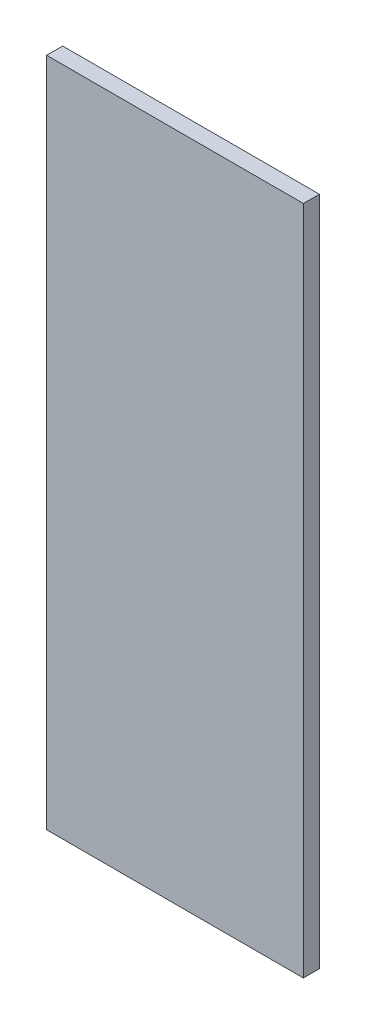
SolidWorks part; units mm, degrees
material "AISI 1020"
ref_plane "Спереди" through (0, 0, 0) normal (0, 0, 1) x (1, 0, 0)
ref_plane "Сверху" through (0, 0, 0) normal (0, 1, 0) x (1, 0, 0)
ref_plane "Справа" through (0, 0, 0) normal (1, 0, 0) x (0, 0, -1)
sketch "Эскиз1" plane through (0, 0, 0) normal (0, 0, 1) x (1, 0, 0)
  line L1 (0, 0) -> (-800, 0)
  line L2 (0, 0) -> (0, 2090)
  line L3 (0, 2090) -> (-800, 2090)
  line L4 (-800, 0) -> (-800, 2090)
  dimension "D1" = 2090
  dimension "D2" = 800
extrude "Бобышка-Вытянуть1" add sketch "Эскиз1" along normal blind 50
